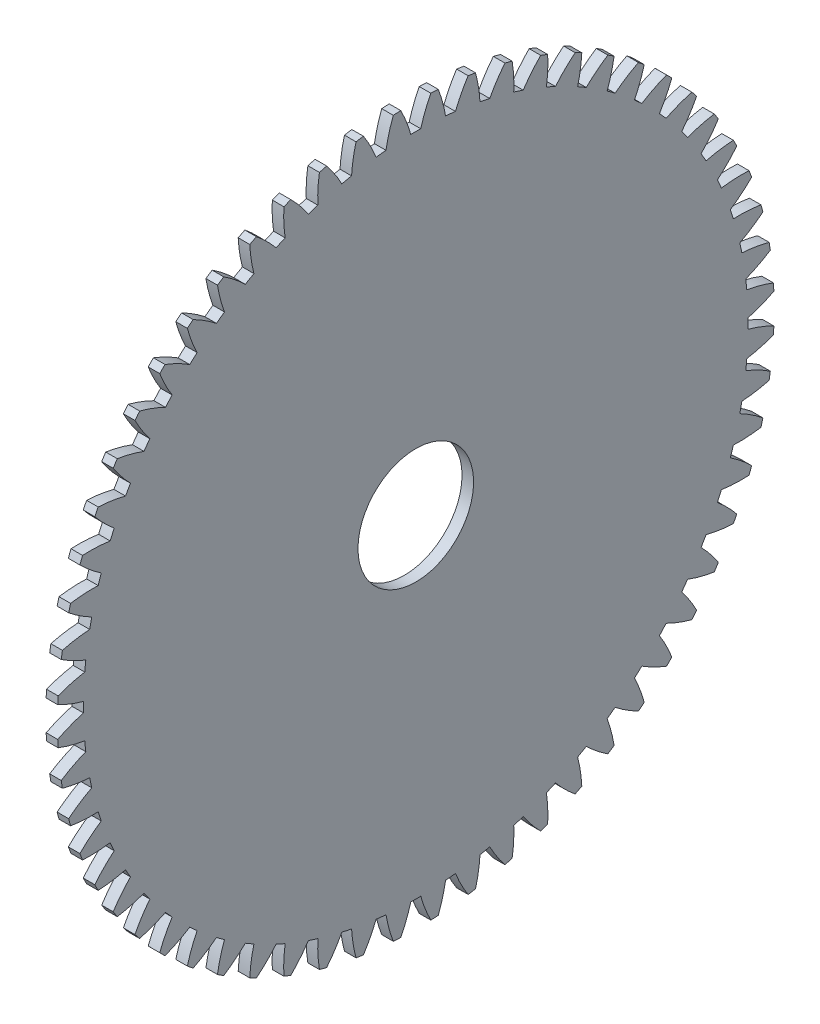
SolidWorks part; units mm, degrees
ref_plane "Plane1" through (0, 0, 0) normal (0, 0, 1) x (1, 0, 0)
ref_plane "Plane2" through (0, 0, 0) normal (0, 1, 0) x (1, 0, 0)
ref_plane "Plane3" through (0, 0, 0) normal (1, 0, 0) x (0, 0, -1)
sketch "HoldingSke" plane through (0, 0, 0) normal (0, 1, 0) x (1, 0, 0)
  line L0 (0, 0) -> (0.5, -0.866)
  line L1 (-15, 0) -> (100, 0) construction
  line L2 (0, 0) -> (-2.1039, 2.3779)
  line L3 (0, 0) -> (-11.863, 4.5341)
  line L4 (0, 0) -> (4.318, 7.479)
  line L5 (0, 0) -> (-46.8476, -17.4728)
  line L6 (0, 0) -> (-0.829, -0.5593)
  line L7 (-2.1039, 2.3779) -> (8.6586, 51.2059)
  line L8 (-76.2, 54.61) -> (-74.4, 54.61)
  line L9 (-71.009, 38.7566) -> (-53.1078, 45.2721)
  line L10 (-76.2, 71.12) -> (104.1128, 71.12)
  line L11 (0, 0) -> (-1, 0)
  line L12 (-76.2, 101.6) -> (-76.162, 101.6)
  line L13 (24.9733, 27.94) -> (52.9518, 28.4284)
  line L14 (24.9733, 27.94) -> (24.9743, 27.94)
  line L15 (24.9733, 27.94) -> (100.4006, 29.5858)
  line L16 (-63.627, -1) -> (-12.827, -1)
  circle A0 centre (0, 0) radius 5
  circle A1 centre (0, 0) radius 28.749
  circle A2 centre (0, 0) radius 37.5
  circle A3 centre (0, 0) radius 5
  dimension "MHD" = 57.498
  dimension "Hub_dia" = 75
  dimension "Bore" = 10
  dimension "MBD" = 10
  dimension "Num_teeth" = 60
  dimension "Pitch" = 1
  dimension "Overall_len" = 50
  dimension "Show_teeth" = 60
  dimension "Thickness" = 1
  dimension "OAL" = 50.0001
  dimension "T_dim" = 1.8
  dimension "Ap" = 20
  dimension "H" = 19.05
  dimension "Pitch_radius" = 180.3128
  dimension "Width" = 1
  dimension "Backlash" = 0.038
  dimension "Addendum_fac" = 1
  dimension "Dedendum_fac" = 1.25
  dimension "Clearance_fac" = 0.25
  dimension "Dedendum_add" = 0.001
  dimension "Module" = 1
sketch "BasProSke" plane through (0, 0, 0) normal (0, 1, 0) x (1, 0, 0)
  line L0 (-10, 0) -> (60, 0) construction
  line L1 (0, 0) -> (0, 31)
  line L2 (0, 0) -> (1, 0)
  line L3 (1, 0) -> (1, 31)
  line L4 (1, 31) -> (0, 31)
  dimension "Thickness" = 1
  dimension "Diameter" = 62
revolve "Base-Revolve" add sketch "BasProSke" angle 360 about L0
sketch "TooCutSke" plane through (0, 0, 0) normal (1, 0, 0) x (0, 0, -1)
  line L1 (0, 0) -> (0, 107) construction
  line L2 (0, 0) -> (-0.8518, 29.9879) construction
  line L3 (0, 0) -> (-3.1393, 59.9006) construction
  line L4 (-0.8518, 29.9879) -> (-1.5696, 29.9503) construction
  arc A0 (0.4302, 28.7458) -> (-0.4302, 28.7458) centre (0, 0) ccw
  arc A1 (1.3127, 30.9976) -> (-1.3127, 30.9976) centre (0, 0) ccw
  circle A2 centre (0, 0) radius 30 construction
  circle A3 centre (0, 0) radius 28.1908 construction
  arc A4 (-0.4302, 28.7458) -> (-1.3127, 30.9976) centre (-11.9871, 25.5153) ccw
  arc A5 (1.3127, 30.9976) -> (0.4302, 28.7458) centre (11.9871, 25.5153) ccw
  dimension "Root_dia" = 57.498
  dimension "Overcut_dia" = 62.0508
  dimension "Pitch_dia" = 60
  dimension "Base_dia" = 56.3816
  dimension "Flank_rad" = 12
  dimension "Half_ang" = 3
  dimension "Half_CT" = 0.7188
extrude "ToothCut" cut sketch "TooCutSke" along normal through all
fillet "Breaks" [suppressed] radius 0.02
fillet "RootFillets" [suppressed] radius 0.251
pattern_circular "TeethCuts" count 60 every 6 about axis through (-10, 0, 0) along (1, 0, 0) of "ToothCut", "RootFillets", "Breaks"
sketch "HubNeaOneSke" plane through (0, 0, 0) normal (-1, 0, 0) x (0, 0, 1)
  circle A0 centre (0, 0) radius 28.749
  dimension "Diameter" = 57.498
extrude "HubNearOne" [suppressed] add sketch "HubNeaOneSke" along normal blind 49.0001
sketch "HubNeaBotSke" plane through (0, 0, 0) normal (-1, 0, 0) x (0, 0, 1)
  circle A0 centre (0, 0) radius 28.749
  dimension "Diameter" = 57.498
extrude "HubNearBoth" [suppressed] add sketch "HubNeaBotSke" along normal blind 24.5
ref_plane "FarPln" through (1, 0, 0) normal (1, 0, 0) x (0, 0, -1)
sketch "HubFarSke" plane through (1, 0, 0) normal (1, 0, 0) x (0, 0, -1)
  circle A0 centre (0, 0) radius 28.749
  dimension "Diameter" = 57.498
extrude "HubFar" [suppressed] add sketch "HubFarSke" along normal blind 24.5
sketch "BorSke" plane through (0, 0, 0) normal (1, 0, 0) x (0, 0, -1)
  circle A0 centre (0, 0) radius 5
  dimension "Diameter" = 10
extrude "Bore" cut sketch "BorSke" along normal mid plane 100.0001
sketch "KeySke" plane through (0, 0, 0) normal (1, 0, 0) x (0, 0, -1)
  line L0 (-2, 0) -> (-2, 6.8)
  line L1 (-2, 6.8) -> (2, 6.8)
  line L2 (2, 6.8) -> (2, 0)
  line L3 (0, 0) -> (0, 34) construction
  line L4 (-2, 0) -> (2, 0)
  dimension "Offset" = 6.8
  dimension "Width" = 4
extrude "Keyway" [suppressed] cut sketch "KeySke" along normal mid plane 100.0001
pattern_circular "Keyway2" [suppressed] count 2 every 90 about axis through (-10, 0, 0) along (1, 0, 0)
equation "' \"Module@HoldingSke\" = 6.35"
equation "' \"Num_teeth@HoldingSke\" = 12"
equation "' \"Ap@HoldingSke\" =  20"
equation "' \"Ap@HoldingSke\" = 20"
equation "' \"Width@HoldingSke\" = 0.5 * 25.4"
equation "' \"Hub_dia@HoldingSke\"= 1 * 25.4"
equation "' \"Hub_dia@HoldingSke\" = 1 * 25.4"
equation "' \"Overall_len@HoldingSke\" = 1.0 * 25.4"
equation "' \"Bore@HoldingSke\" = 0.75 * 25.4"
equation "' \"T_dim@HoldingSke\" = 0.1 * 25.4"
equation "' \"Width@KeySke\" = 0.25 * 25.4"
equation "' \"Show_teeth@HoldingSke\" = 13"
equation "' \"Backlash@HoldingSke\" = 0.009 * 25.4"
equation "' \"Addendum_fac@HoldingSke\" = 1.0"
equation "' \"Dedendum_fac@HoldingSke\" = 1.25"
equation "' \"Dedendum_add@HoldingSke\" = 0.00005 * 25.4"
equation "' \"Clearance_fac@HoldingSke\" = 0.25"
equation "\"Pitch@HoldingSke\" = 1 / \"Module@HoldingSke\""
equation "\"Overcut_dia@TooCutSke\" = (\"Num_teeth@HoldingSke\" + 2 * \"Addendum_fac@HoldingSke\") / \"Pitch@HoldingSke\" + 0.002 * 25.4"
equation "\"Pitch_dia@TooCutSke\" = \"Num_teeth@HoldingSke\" / \"Pitch@HoldingSke\""
equation "\"Base_dia@TooCutSke\" = \"Num_teeth@HoldingSke\" / \"Pitch@HoldingSke\" * cos((\"Ap@HoldingSke\"  * 3.14159265 / 180))"
equation "\"Root_dia@TooCutSke\" = (\"Num_teeth@HoldingSke\" + 2) / \"Pitch@HoldingSke\" - 2 * (\"Addendum_fac@HoldingSke\" + \"Dedendum_fac@HoldingSke\") / \"Pitch@HoldingSke\" - \"Dedendum_add@HoldingSke\" * 2"
equation "\"Half_ang@TooCutSke\" = 180 / \"Num_teeth@HoldingSke\""
equation "\"Half_CT@TooCutSke\" = \"Num_teeth@HoldingSke\" / \"Pitch@HoldingSke\" * sin((3.14159265 / 2 / \"Num_teeth@HoldingSke\")) / 2 - 7 * \"Backlash@HoldingSke\" / 4"
equation "\"Flank_rad@TooCutSke\" = \"Num_teeth@HoldingSke\" / \"Pitch@HoldingSke\" / 5"
equation "\"Radius@RootFillets\" = \"Clearance_fac@HoldingSke\" / \"Pitch@HoldingSke\" + \"Dedendum_add@HoldingSke\""
equation "\"Break_rad@Breaks\" = 0.02 / \"Pitch@HoldingSke\""
equation "\"Thickness@HoldingSke\" = \"Width@HoldingSke\""
equation "\"OAL@HoldingSke\" = \"Thickness@HoldingSke\""
equation "\"MHD@HoldingSke\" = (\"Num_teeth@HoldingSke\" + 2) / \"Pitch@HoldingSke\" - 2 * (\"Addendum_fac@HoldingSke\" + \"Dedendum_fac@HoldingSke\")  / \"Pitch@HoldingSke\" - \"Dedendum_add@HoldingSke\" * 2"
equation "\"MBD@HoldingSke\" = (\"Num_teeth@HoldingSke\" + 2) / \"Pitch@HoldingSke\" - 2 * (\"Addendum_fac@HoldingSke\" + \"Dedendum_fac@HoldingSke\")  / \"Pitch@HoldingSke\" - \"Dedendum_add@HoldingSke\" * 2 - 0.002 * 25.4"
equation "\"MHD@HoldingSke\" = ((sgn( \"MHD@HoldingSke\" - \"Hub_dia@HoldingSke\" )-1)*( \"MHD@HoldingSke\" - \"Hub_dia@HoldingSke\" ))/-2+ \"Hub_dia@HoldingSke\""
equation "\"MBD@HoldingSke\" = ((sgn( \"MBD@HoldingSke\" - \"Bore@HoldingSke\" )-1)*( \"MBD@HoldingSke\" - \"Bore@HoldingSke\" ))/-2+ \"Bore@HoldingSke\""
equation "\"OAL@HoldingSke\" = ((sgn( \"OAL@HoldingSke\" - \"Overall_len@HoldingSke\" )+1)*( \"OAL@HoldingSke\" - \"Overall_len@HoldingSke\" ))/2 + \"Overall_len@HoldingSke\" + 0.000002 * 25.4"
equation "\"Num_teeth@TeethCuts\" = int( \"Show_teeth@HoldingSke\" ) + 1"
equation "\"Num_teeth@TeethCuts\" = ((sgn( \"Num_teeth@TeethCuts\" - \"Num_teeth@HoldingSke\" )-1)*( \"Num_teeth@TeethCuts\" - \"Num_teeth@HoldingSke\" ))/-2+ \"Num_teeth@HoldingSke\""
equation "\"Num_teeth@TeethCuts\" = ((sgn( \"Num_teeth@TeethCuts\" - 2.0)+1)*( \"Num_teeth@TeethCuts\" - 2.0))/2 +2.0"
equation "\"Angle@TeethCuts\" = 360.0 / \"Num_teeth@HoldingSke\""
equation "\"Diameter@BasProSke\" = (\"Num_teeth@HoldingSke\" + 2 * \"Addendum_fac@HoldingSke\") / \"Pitch@HoldingSke\""
equation "\"Thickness@BasProSke\"  = \"Thickness@HoldingSke\""
equation "' \"Fillet_rad@BasProSke\" =  \"Thickness@HoldingSke\" * 0.05"
equation "' \"Fillet_rad@BasProSke\" = \"Thickness@HoldingSke\" * 0.05"
equation "\"MHD@HoldingSke\" = ((sgn( \"MHD@HoldingSke\" - \"Root_dia@TooCutSke\" )-1)*( \"MHD@HoldingSke\" - \"Root_dia@TooCutSke\" ))/-2+ \"Root_dia@TooCutSke\""
equation "\"Diameter@HubNeaOneSke\" = \"MHD@HoldingSke\""
equation "\"Length@HubNearOne\" = \"OAL@HoldingSke\" - \"Thickness@BasProSke\""
equation "\"Diameter@HubNeaBotSke\" = \"MHD@HoldingSke\""
equation "\"Length@HubNearBoth\" = ( \"OAL@HoldingSke\" - \"Thickness@BasProSke\" ) / 2.0"
equation "\"Thickness@FarPln\" = \"Thickness@BasProSke\""
equation "\"Diameter@HubFarSke\" = \"MHD@HoldingSke\""
equation "\"Length@HubFar\" = ( \"OAL@HoldingSke\" - \"Thickness@BasProSke\" ) / 2.0"
equation "\"Diameter@BorSke\" = \"MBD@HoldingSke\""
equation "\"D1@Bore\" = \"OAL@HoldingSke\" * 2.0"
equation "\"D1@Keyway\" = \"OAL@HoldingSke\" * 2.0"
equation "\"Offset@KeySke\" = \"T_dim@HoldingSke\" + \"MBD@HoldingSke\" / 2.0"
